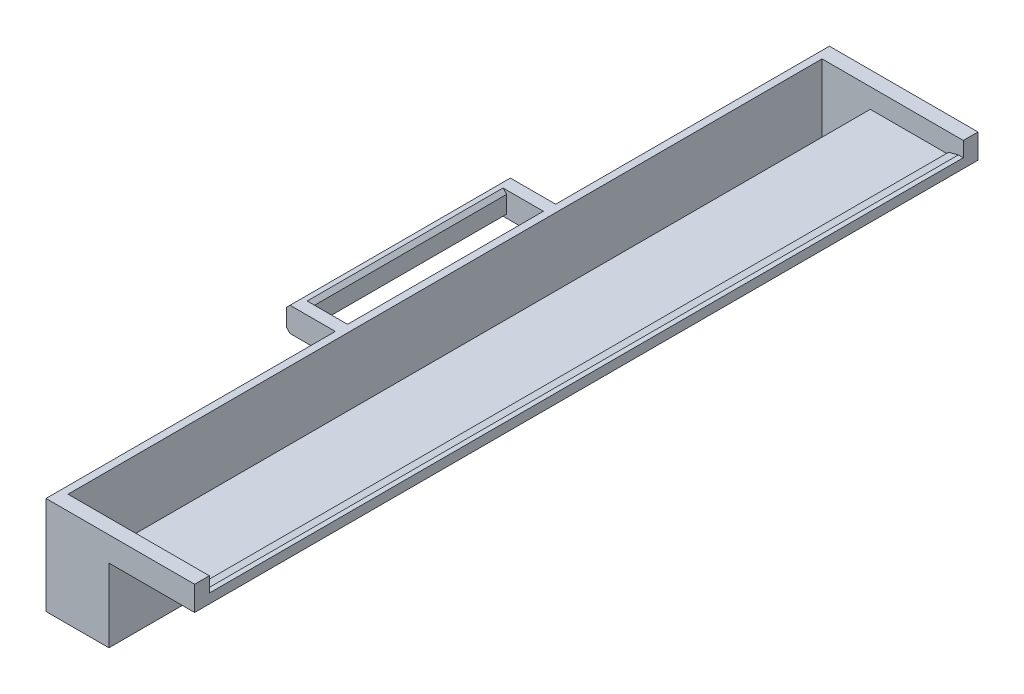
SolidWorks part; units mm, degrees
ref_plane "Front Plane" through (0, 0, 0) normal (0, 0, 1) x (1, 0, 0)
ref_plane "Top Plane" through (0, 0, 0) normal (0, 1, 0) x (1, 0, 0)
ref_plane "Right Plane" through (0, 0, 0) normal (1, 0, 0) x (0, 0, -1)
sketch "Sketch1" plane through (0, 0, 0) normal (0, 0, 1) x (1, 0, 0)
  line L1 (-36.83, -4.9276) -> (7.62, -4.9276)
  line L2 (7.62, -4.9276) -> (7.62, 0)
  line L3 (7.62, 0) -> (0, 0)
  line L4 (0, 0) -> (0, -2.3876)
  line L5 (0, -2.3876) -> (-29.21, -2.3876)
  line L8 (-36.83, -4.9276) -> (-36.83, -43.0276)
  line L9 (-69.4725, -43.0276) -> (-69.4725, 7.7724)
  line L10 (-69.4725, 7.7724) -> (-65.6625, 7.7724)
  line L11 (-69.4725, -43.0276) -> (-36.83, -43.0276)
  line L12 (-65.6625, 7.7724) -> (-65.6625, -39.2176)
  line L13 (-65.6625, -39.2176) -> (-40.64, -39.2176)
  line L14 (-40.64, -39.2176) -> (-40.64, -2.3876)
  line L15 (-40.64, -2.3876) -> (-29.21, -2.3876)
  dimension "D1" = 38.1
  dimension "D2" = 2.54
  dimension "D3" = 4.9276
  dimension "D4" = 7.62
  dimension "D5" = 50.8
  dimension "D6" = 44.45
  dimension "D7" = 3.81
  dimension "D8" = 3.81
  dimension "D9" = 3.81
  dimension "D10" = 32.6425
extrude "Boss-Extrude1" add sketch "Sketch1" along normal blind 406.4 contours L1 L2 L3 L4 L5 L15 L14 L13 L12 L10 L9 L11 L8
sketch "Sketch2" plane through (0, 0, 406.4) normal (0, 0, 1) x (1, 0, 0)
sketch "Sketch3" plane through (0, -4.9276, 0) normal (0, -1, 0) x (-1, 0, 0)
  line L1 (-7.62, 0) -> (36.83, 0)
  line L2 (-7.62, 0) -> (-7.62, -406.4)
  line L3 (-7.62, -406.4) -> (36.83, -406.4)
  line L4 (36.83, 0) -> (36.83, -406.4)
sketch "Sketch4" plane through (0, -2.3876, 0) normal (0, 1, 0) x (1, 0, 0)
  line L1 (7.62, -406.4) -> (-65.6625, -406.4)
  line L2 (7.62, -406.4) -> (7.62, -398.78)
  line L3 (7.62, -398.78) -> (-65.6625, -398.78)
  line L4 (-65.6625, -406.4) -> (-65.6625, -398.78)
  line L6 (7.62, 0) -> (-65.6625, 0)
  line L7 (7.62, 0) -> (7.62, -7.62)
  line L8 (7.62, -7.62) -> (-65.6625, -7.62)
  line L9 (-65.6625, 0) -> (-65.6625, -7.62)
  dimension "D1" = 7.62
  dimension "D2" = 7.62
extrude "Boss-Extrude4" add sketch "Sketch4" along normal up to vertex
sketch "Sketch7" plane through (0, 0, 406.4) normal (0, 0, 1) x (1, 0, 0)
  line L0 (-65.6625, -39.2176) -> (-40.64, -39.2176) construction
  line L1 (-40.64, -39.2176) -> (-40.64, -2.3876) construction
  line L2 (-65.6625, -2.3876) -> (-40.64, -2.3876) construction
  line L3 (-65.6625, -2.3876) -> (-65.6625, -39.2176) construction
  line L4 (-65.6625, -39.2176) -> (-40.64, -39.2176)
  line L5 (-40.64, -39.2176) -> (-40.64, -2.3876)
  line L6 (-65.6625, -2.3876) -> (-40.64, -2.3876)
  line L7 (-65.6625, -2.3876) -> (-65.6625, -39.2176)
extrude "Boss-Extrude5" add sketch "Sketch7" against normal up to vertex
sketch "Sketch11" plane through (0, 0, 0) normal (0, 0, -1) x (-1, 0, 0)
  line L0 (65.6625, -2.3876) -> (65.6625, -39.2176) construction
  line L1 (65.6625, -39.2176) -> (40.64, -39.2176) construction
  line L2 (40.64, -2.3876) -> (65.6625, -2.3876) construction
  line L3 (40.64, -39.2176) -> (40.64, -2.3876) construction
  line L4 (65.6625, -2.3876) -> (65.6625, -39.2176)
  line L5 (65.6625, -39.2176) -> (40.64, -39.2176)
  line L6 (40.64, -2.3876) -> (65.6625, -2.3876)
  line L7 (40.64, -39.2176) -> (40.64, -2.3876)
extrude "Boss-Extrude6" add sketch "Sketch11" against normal up to vertex
sketch "Sketch15" plane through (0, 7.7724, 0) normal (0, 1, 0) x (1, 0, 0)
  line L0 (-69.4725, -203.2) -> (-166.9903, -203.2) construction
  line L1 (-69.4725, -406.4) -> (-69.4725, 0) construction
  line L2 (-69.4725, -256.3081) -> (-69.4725, -249.9581)
  line L3 (-69.4725, -148.3581) -> (-88.5225, -148.3581)
  line L4 (-88.5225, -148.3581) -> (-88.5225, -249.9581)
  line L5 (-88.5225, -249.9581) -> (-69.4725, -249.9581)
  line L6 (-69.4725, -148.3581) -> (-69.4725, -142.0081)
  line L7 (-69.4725, -142.0081) -> (-94.8725, -142.0081)
  line L8 (-94.8725, -142.0081) -> (-94.8725, -256.3081)
  line L9 (-69.4725, -256.3081) -> (-94.8725, -256.3081)
  dimension "D1" = 6.35
  dimension "D2" = 6.35
  dimension "D3" = 6.35
  dimension "D4" = 114.3
  dimension "D5" = 25.4
extrude "Boss-Extrude7" add sketch "Sketch15" against normal blind 12.7
chamfer "Chamfer3" distance 1.905 angle 45 4 edges at (-88.5225, -4.9276, 199.1581) (-94.8725, -4.9276, 199.1581) (-94.8725, 7.7724, 199.1581) (-88.5225, 7.7724, 199.1581)
chamfer "Chamfer4" distance 5.08 angle 15 1 edges at (0, 0, 203.2)
